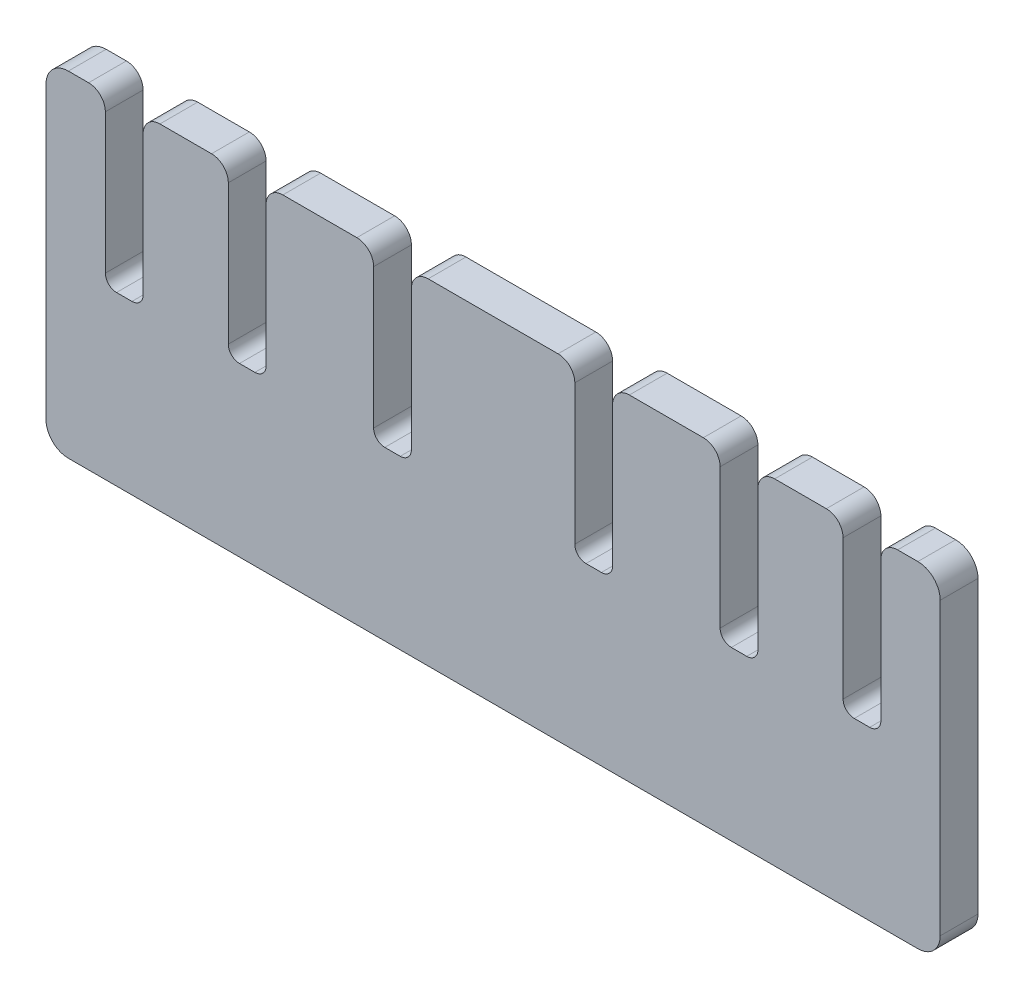
SolidWorks part; units mm, degrees
ref_plane "Front Plane" through (0, 0, 0) normal (0, 0, 1) x (1, 0, 0)
ref_plane "Top Plane" through (0, 0, 0) normal (0, 1, 0) x (1, 0, 0)
ref_plane "Right Plane" through (0, 0, 0) normal (1, 0, 0) x (0, 0, -1)
sketch "Sketch1" plane through (0, 0, 0) normal (0, 0, 1) x (1, 0, 0)
  line L1 (-50.8, -19.05) -> (50.8, -19.05)
  line L2 (-50.8, -19.05) -> (-50.8, 19.05)
  line L3 (-50.8, 19.05) -> (50.8, 19.05)
  line L4 (50.8, -19.05) -> (50.8, 19.05)
  line L5 (-50.8, -19.05) -> (50.8, 19.05) construction
  line L6 (-50.8, 19.05) -> (50.8, -19.05) construction
  point P0 (0, 0)
  dimension "D1" = 101.6
  dimension "D2" = 38.1
extrude "Boss-Extrude1" add sketch "Sketch1" along normal blind 4.2926
fillet "Fillet1" radius 2.54 4 edges at (50.8, -19.05, 2.1463) (50.8, 19.05, 2.1463) (-50.8, -19.05, 2.1463) (-50.8, 19.05, 2.1463)
sketch "Sketch2" plane through (0, 0, 4.2926) normal (0, 0, 1) x (1, 0, 0)
  line L0 (48.26, 19.05) -> (-48.26, 19.05) construction
  line L1 (-44.0563, 19.05) -> (-39.7637, 19.05)
  line L2 (-44.0563, 19.05) -> (-44.0563, 0)
  line L3 (-44.0563, 0) -> (-39.7637, 0)
  line L4 (-39.7637, 19.05) -> (-39.7637, 0)
  line L5 (-44.0563, 19.05) -> (-39.7637, 0) construction
  line L6 (-44.0563, 0) -> (-39.7637, 19.05) construction
  line L7 (-30.0863, 19.05) -> (-25.7937, 19.05)
  line L8 (-30.0863, 19.05) -> (-30.0863, 0)
  line L9 (-30.0863, 0) -> (-25.7937, 0)
  line L10 (-25.7937, 19.05) -> (-25.7937, 0)
  line L11 (-30.0863, 19.05) -> (-25.7937, 0) construction
  line L12 (-30.0863, 0) -> (-25.7937, 19.05) construction
  line L13 (-13.5763, 19.05) -> (-9.2837, 19.05)
  line L14 (-13.5763, 19.05) -> (-13.5763, 0)
  line L15 (-13.5763, 0) -> (-9.2837, 0)
  line L16 (-9.2837, 19.05) -> (-9.2837, 0)
  line L17 (-13.5763, 19.05) -> (-9.2837, 0) construction
  line L18 (-13.5763, 0) -> (-9.2837, 19.05) construction
  line L19 (9.2837, 19.05) -> (13.5763, 19.05)
  line L20 (9.2837, 19.05) -> (9.2837, 0)
  line L21 (9.2837, 0) -> (13.5763, 0)
  line L22 (13.5763, 19.05) -> (13.5763, 0)
  line L23 (9.2837, 19.05) -> (13.5763, 0) construction
  line L24 (9.2837, 0) -> (13.5763, 19.05) construction
  line L25 (25.7937, 19.05) -> (30.0863, 19.05)
  line L26 (25.7937, 19.05) -> (25.7937, 0)
  line L27 (25.7937, 0) -> (30.0863, 0)
  line L28 (30.0863, 19.05) -> (30.0863, 0)
  line L29 (25.7937, 19.05) -> (30.0863, 0) construction
  line L30 (25.7937, 0) -> (30.0863, 19.05) construction
  line L31 (39.7637, 19.05) -> (44.0563, 19.05)
  line L32 (39.7637, 19.05) -> (39.7637, 0)
  line L33 (39.7637, 0) -> (44.0563, 0)
  line L34 (44.0563, 19.05) -> (44.0563, 0)
  line L35 (39.7637, 19.05) -> (44.0563, 0) construction
  line L36 (39.7637, 0) -> (44.0563, 19.05) construction
  line L37 (-50.8, 16.51) -> (-50.8, -16.51) construction
  line L38 (50.8, -16.51) -> (50.8, 16.51) construction
  point P0 (-41.91, 9.525)
  point P5 (-27.94, 9.525)
  point P10 (-11.43, 9.525)
  point P15 (11.43, 9.525)
  point P20 (27.94, 9.525)
  point P25 (41.91, 9.525)
  point P37 (0, 0)
  point P38 (-10.9904, 11.7362)
  point P39 (11.2947, 13.4083)
  point P40 (25.8569, 10.5101)
  dimension "D1" = 4.2926
  dimension "D2" = 4.2926
  dimension "D3" = 4.2926
  dimension "D4" = 4.2926
  dimension "D5" = 4.2926
  dimension "D6" = 4.2926
  dimension "D7" = 8.89
  dimension "D8" = 8.89
  dimension "D9" = 19.05
  dimension "D10" = 11.43
  dimension "D11" = 16.51
  dimension "D12" = 11.43
  dimension "D13" = 16.51
extrude "Cut-Extrude1" cut sketch "Sketch2" against normal blind 4.2926
fillet "Fillet2" radius 1.905 12 edges at (-44.0563, 19.05, 2.1463) (44.0563, 19.05, 2.1463) (30.0863, 19.05, 2.1463) (13.5763, 19.05, 2.1463) (39.7637, 19.05, 2.1463) (25.7937, 19.05, 2.1463) (9.2837, 19.05, 2.1463) (-9.2837, 19.05, 2.1463) (-13.5763, 19.05, 2.1463) (-25.7937, 19.05, 2.1463) (-30.0863, 19.05, 2.1463) (-39.7637, 19.05, 2.1463)
fillet "Fillet3" radius 1.27 12 edges at (44.0563, 0, 2.1463) (30.0863, 0, 2.1463) (13.5763, 0, 2.1463) (39.7637, 0, 2.1463) (25.7937, 0, 2.1463) (9.2837, 0, 2.1463) (-9.2837, 0, 2.1463) (-13.5763, 0, 2.1463) (-25.7937, 0, 2.1463) (-30.0863, 0, 2.1463) (-39.7637, 0, 2.1463) (-44.0563, 0, 2.1463)
equation "\"thick\"=0.169"
equation "\"D1@Boss-Extrude1\"=\"thick\""
equation "\"D1@Sketch2\"=\"thick\""
equation "\"D2@Sketch2\"=\"thick\""
equation "\"D3@Sketch2\"=\"thick\""
equation "\"D4@Sketch2\"=\"thick\""
equation "\"D5@Sketch2\"=\"thick\""
equation "\"D6@Sketch2\"=\"thick\""
